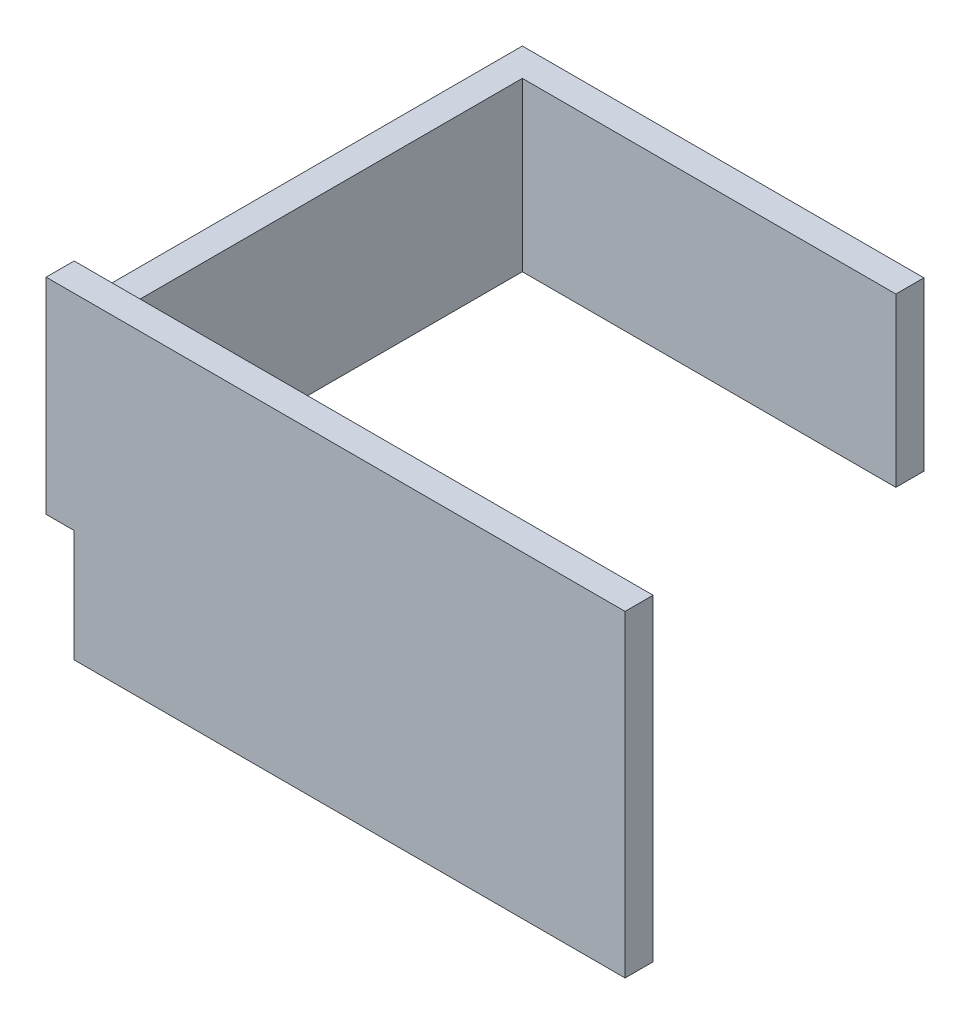
SolidWorks part; units mm, degrees
ref_plane "前视基准面" through (0, 0, 0) normal (0, 0, 1) x (1, 0, 0)
ref_plane "上视基准面" through (0, 0, 0) normal (0, 1, 0) x (1, 0, 0)
ref_plane "右视基准面" through (0, 0, 0) normal (1, 0, 0) x (0, 0, -1)
other "Configuration Table"
sketch "草图1" plane through (0, 0, 0) normal (0, 1, 0) x (1, 0, 0)
  line L1 (0, 0) -> (59, 0)
  line L2 (0, 0) -> (0, -3)
  line L3 (0, -3) -> (59, -3)
  line L4 (59, 0) -> (59, -3)
  dimension "D1" = 3
  dimension "D2" = 59
extrude "凸台-拉伸1" add sketch "草图1" along normal blind 34
sketch "草图2" plane through (0, 34, 0) normal (0, 1, 0) x (1, 0, 0)
  line L1 (0, -3) -> (-3, -3)
  line L2 (0, -3) -> (0, 45)
  line L3 (0, 45) -> (-3, 45)
  line L4 (-3, -3) -> (-3, 45)
  dimension "D1" = 45
  dimension "D2" = 3
extrude "凸台-拉伸2" add sketch "草图2" against normal blind 22
sketch "草图3" plane through (0, 34, 0) normal (0, 1, 0) x (1, 0, 0)
  line L0 (0, 0) -> (0, 45) construction
  line L1 (-3, 45) -> (40, 45)
  line L2 (-3, 45) -> (-3, 48)
  line L3 (-3, 48) -> (40, 48)
  line L4 (40, 45) -> (40, 48)
  dimension "D1" = 40
  dimension "D2" = 3
extrude "凸台-拉伸3" add sketch "草图3" against normal up to surface (22 mm away) up to face at (-1.2, 12, -16.8)
sketch "草图4" plane through (40, 0, 0) normal (1, 0, 0) x (0, 0, -1)
  line L0 (0, 34) -> (0, 0) construction
  line L1 (48, 34) -> (0, 34)
  line L2 (48, 34) -> (48, 29.9356)
  line L3 (48, 29.9356) -> (0, 29.9356)
  line L4 (0, 34) -> (0, 29.9356)
  dimension "D1" = 4.0644
extrude "切除-拉伸1" cut sketch "草图4" against normal blind 89
